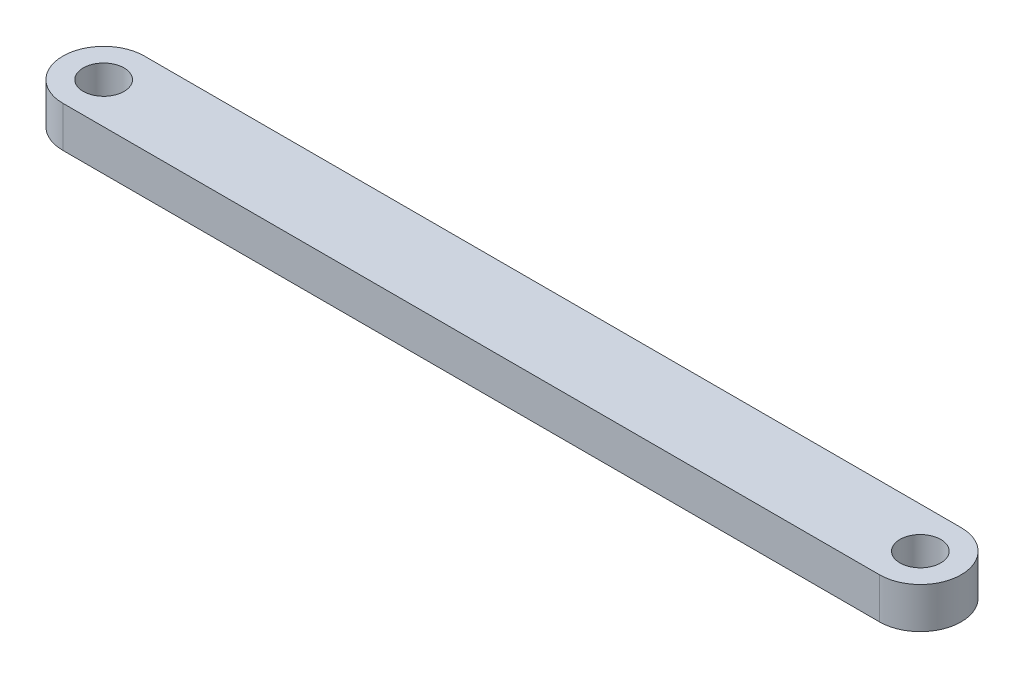
SolidWorks part; units mm, degrees
ref_plane "前视基准面" through (0, 0, 0) normal (0, 0, 1) x (1, 0, 0)
ref_plane "上视基准面" through (0, 0, 0) normal (0, 1, 0) x (1, 0, 0)
ref_plane "右视基准面" through (0, 0, 0) normal (1, 0, 0) x (0, 0, -1)
sketch "草图1" plane through (0, 0, 0) normal (0, 1, 0) x (1, 0, 0)
  line L0 (0, 3) -> (-60, 3)
  line L1 (68.0174, 0) -> (-68.0174, 0) construction
  line L2 (0, -3) -> (-60, -3)
  circle A0 centre (0, 0) radius 1.5
  arc A1 (0, -3) -> (0, 3) centre (0, 0) ccw
  arc A2 (-60, 3) -> (-60, -3) centre (-60, 0) ccw
  circle A3 centre (-60, 0) radius 1.5
  point P9 (0, 0)
  dimension "D1" = 3
  dimension "D2" = 6
  dimension "D3" = 3
  dimension "D4" = 60
extrude "凸台-拉伸1" add sketch "草图1" along normal blind 3
